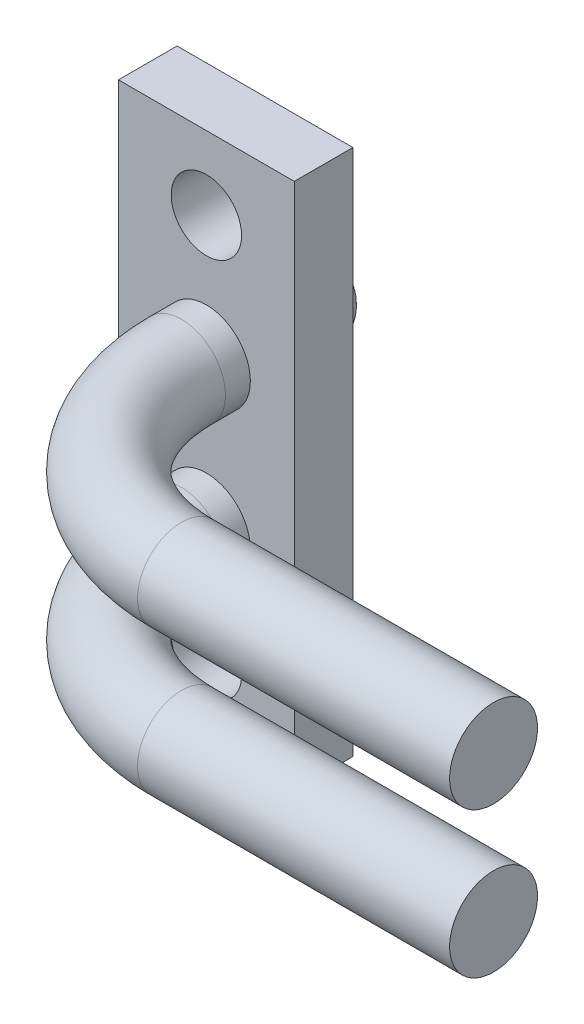
SolidWorks part; units mm, degrees
ref_plane "Front Plane" through (0, 0, 0) normal (0, 0, 1) x (1, 0, 0)
ref_plane "Top Plane" through (0, 0, 0) normal (0, 1, 0) x (1, 0, 0)
ref_plane "Right Plane" through (0, 0, 0) normal (1, 0, 0) x (0, 0, -1)
sketch "Sketch1" plane through (0, 0, 0) normal (0, 0, 1) x (1, 0, 0)
  line L1 (-3, -9) -> (3, -9)
  line L2 (-3, -9) -> (-3, 9)
  line L3 (-3, 9) -> (3, 9)
  line L4 (3, -9) -> (3, 9)
  line L5 (-3, -9) -> (3, 9) construction
  line L6 (-3, 9) -> (3, -9) construction
  point P0 (0, 0)
  dimension "D1" = 18
  dimension "D2" = 6
extrude "Boss-Extrude1" add sketch "Sketch1" along normal blind 2
sketch "Sketch2" plane through (0, 0, 0) normal (0, 0, -1) x (-1, 0, 0)
  circle A0 centre (0, 2.35) radius 1.5
  circle A1 centre (0, -2.62) radius 1.5
  dimension "D2" = 3
  dimension "D1" = 4.97
  dimension "D3" = 2.35
extrude "Boss-Extrude2" add sketch "Sketch2" along normal blind 2.5
sketch "Sketch6" plane through (-3, 0, 0) normal (-1, 0, 0) x (0, 0, 1)
  line L0 (0, 9) -> (0, -9) construction
  line L1 (-4.7845, -0.5369) -> (-2.1, -0.5369)
  line L2 (-4.7845, -0.5369) -> (-4.7845, -5.8804)
  line L3 (-4.7845, -5.8804) -> (-2.1, -5.8804)
  line L4 (-2.1, -0.5369) -> (-2.1, -5.8804)
  dimension "D1" = 2.1
extrude "Cut-Extrude2" cut sketch "Sketch6" against normal blind 10
fillet "Fillet1" radius 1.5 2 edges at (-1.5, 2.35, -2.5) (0, -4.12, -2.1)
sketch "Sketch3" plane through (0, 0, 2) normal (0, 0, 1) x (1, 0, 0)
  circle A0 centre (0, -2.62) radius 1.5 construction
  circle A1 centre (0, 2.35) radius 1.5 construction
  circle A2 centre (0, -2.62) radius 1.5
  circle A3 centre (0, 2.35) radius 1.5
ref_plane "Plane1" through (0, 2.35, 0) normal (0, 1, 0) x (-1, 0, 0)
sketch "Sketch4" plane through (0, 2.35, 0) normal (0, 1, 0) x (-1, 0, 0)
  line L0 (0, 2) -> (0, 2.85)
  line L1 (1.5, 2) -> (-1.5, 2) construction
  line L2 (-6, 8.85) -> (-16.65, 8.85)
  arc A0 (0, 2.85) -> (-6, 8.85) centre (-6, 2.85) ccw
  point P8 (0, 8.85)
  dimension "D3" = 6
  dimension "D1" = 16.65
  dimension "D2" = 6.85
sweep "Sweep1" add profiles "Sketch3" path "Sketch4"
sketch "Sketch5" plane through (0, 0, 2) normal (0, 0, 1) x (1, 0, 0)
  line L0 (0, 0) -> (3, 0) construction
  line L1 (3, -9) -> (3, 9) construction
  line L2 (0, -6.5) -> (0, 6.5) construction
  line L3 (3, 9) -> (-3, 9) construction
  circle A0 centre (0, 6.5) radius 1.2
  circle A1 centre (0, -6.5) radius 1.2
  dimension "D1" = 2.4
  dimension "D2" = 2.5
extrude "Cut-Extrude1" cut sketch "Sketch5" against normal through all
